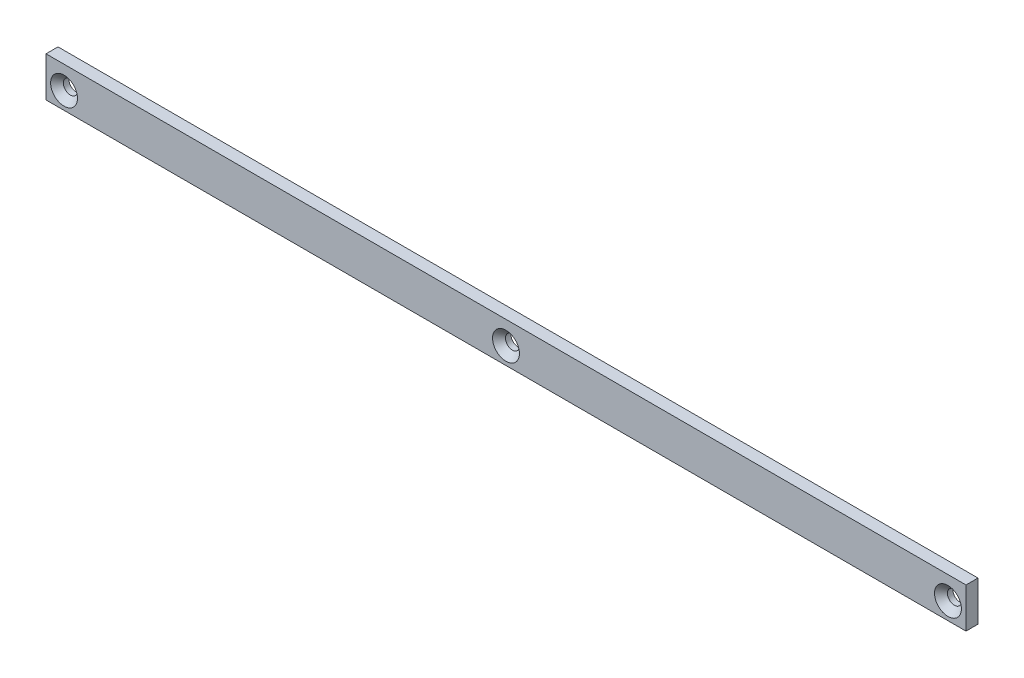
SolidWorks part; units mm, degrees
ref_plane "Alzado" through (0, 0, 0) normal (0, 0, 1) x (1, 0, 0)
ref_plane "Planta" through (0, 0, 0) normal (0, 1, 0) x (1, 0, 0)
ref_plane "Vista lateral" through (0, 0, 0) normal (1, 0, 0) x (0, 0, -1)
sketch "Croquis1" plane through (0, 0, 0) normal (0, 0, 1) x (1, 0, 0)
  line L1 (115, 0) -> (-115, 0)
  line L2 (115, 0) -> (115, 10)
  line L3 (115, 10) -> (-115, 10)
  line L4 (-115, 0) -> (-115, 10)
  circle A0 centre (0, 4.2793) radius 1.75
  circle A1 centre (-110.4907, 4.2793) radius 1.7688
  circle A2 centre (110.4907, 4.2793) radius 1.75
extrude "Saliente-Extruir1" add sketch "Croquis1" along normal blind 3 contours L3 L4 L1 L2 | A2 | A0 | A1
hole_wizard "Refrentado para tornillo tapón con cabeza plana de clavija de M31" positions "Croquis2" profile "Croquis3" countersink size "M3" standard "Ansi Metric" end condition through all
sketch "Croquis2" plane through (0, 0, 3) normal (0, 0, 1) x (1, 0, 0)
  point P0 (-110.4907, 4.2793)
  point P3 (0, 4.2793)
  point P6 (110.4907, 4.2793)
sketch "Croquis3" plane through (-110.4907, 4.2793, 3) normal (1, 0, 0) x (0, -1, 0)
  line L0 (0, 0) -> (0, 3)
  line L1 (0, 3) -> (1.7, 3)
  line L2 (1.7, 3) -> (1.7, 1.66)
  line L3 (1.7, 1.66) -> (3.36, 0)
  line L5 (3.36, 0) -> (0, 0)
  line L6 (-1.7, 1.66) -> (-3.36, 0) construction
  line L11 (0, -6.35) -> (0, 107.95) construction
  dimension "Diámetro de taladro hasta el siguiente" = 3.4
  dimension "Profundidad de taladro hasta el siguiente" = 3
  dimension "Diámetro de avellanado cercano" = 6.72
  dimension "Ángulo de avellanado cercano" = 90
